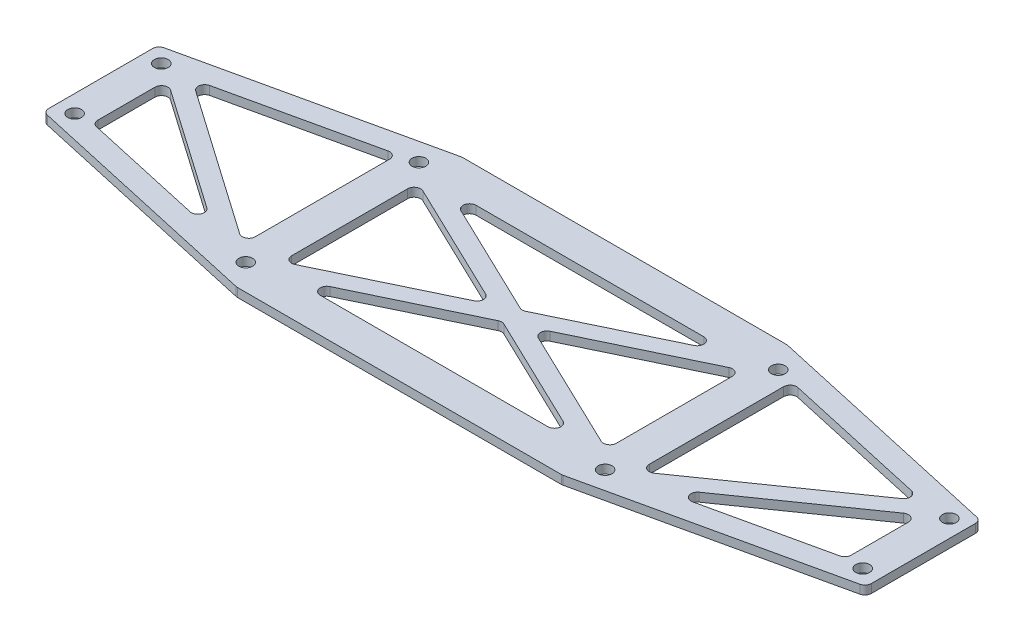
SolidWorks part; units mm, degrees
material "Thornel Mat VMA"
ref_plane "前视基准面" through (0, 0, 0) normal (0, 0, 1) x (1, 0, 0)
ref_plane "上视基准面" through (0, 0, 0) normal (0, 1, 0) x (1, 0, 0)
ref_plane "右视基准面" through (0, 0, 0) normal (1, 0, 0) x (0, 0, -1)
other "Configuration Table"
sketch "草图1" plane through (0, 0, 0) normal (0, 1, 0) x (1, 0, 0)
  line L1 (-95, 26) -> (95, 26)
  line L2 (-95, 26) -> (-95, -26)
  line L3 (-95, -26) -> (95, -26)
  line L4 (95, 26) -> (95, -26)
  line L5 (-95, 26) -> (95, -26) construction
  line L6 (-95, -26) -> (95, 26) construction
  line L7 (-91, 10) -> (91, 10) construction
  line L8 (-91, 10) -> (-91, -10) construction
  line L9 (-91, -10) -> (91, -10) construction
  line L10 (91, 10) -> (91, -10) construction
  line L11 (-91, 10) -> (91, -10) construction
  line L12 (-91, -10) -> (91, 10) construction
  line L13 (-41.5, 20) -> (41.5, 20) construction
  line L14 (-41.5, 20) -> (-41.5, -20) construction
  line L15 (-41.5, -20) -> (41.5, -20) construction
  line L16 (41.5, 20) -> (41.5, -20) construction
  line L17 (-41.5, 20) -> (41.5, -20) construction
  line L18 (-41.5, -20) -> (41.5, 20) construction
  line L19 (-37.5, 18) -> (37.5, 18)
  line L20 (-37.5, 18) -> (-37.5, -18)
  line L21 (-37.5, -18) -> (37.5, -18)
  line L22 (37.5, 18) -> (37.5, -18)
  line L23 (-37.5, 18) -> (37.5, -18) construction
  line L24 (-37.5, -18) -> (37.5, 18) construction
  circle A0 centre (91, -10) radius 1.6
  circle A1 centre (91, 10) radius 1.6
  circle A2 centre (-91, 10) radius 1.6
  circle A3 centre (-91, -10) radius 1.6
  circle A4 centre (41.5, -20) radius 1.6
  circle A5 centre (-41.5, -20) radius 1.6
  circle A6 centre (-41.5, 20) radius 1.6
  circle A7 centre (41.5, 20) radius 1.6
  point P0 (0, 0)
  point P6 (0, 0)
  point P15 (0, 0)
  point P24 (0, 0)
  dimension "D3" = 3.2
  dimension "D1" = 182
  dimension "D2" = 20
  dimension "D4" = 4
  dimension "D5" = 40
  dimension "D6" = 83
  dimension "D7" = 6
  dimension "D8" = 4
  dimension "D9" = 4
extrude "凸台-拉伸1" add sketch "草图1" along normal blind 2
sketch "草图2" plane through (0, 2, 0) normal (0, 1, 0) x (1, 0, 0)
  line L0 (95, 13.2071) -> (37.5601, 26)
  line L1 (95, -26) -> (95, 26) construction
  line L2 (95, 26) -> (-95, 26) construction
  line L3 (37.5601, 26) -> (95, 26)
  line L4 (95, 26) -> (95, 13.2071)
  line L5 (0, 0) -> (0, 43.9826) construction
  line L6 (0, 0) -> (28.9359, 0) construction
  line L7 (37.5601, -26) -> (95, -26)
  line L8 (95, -13.2071) -> (37.5601, -26)
  line L9 (95, -26) -> (95, -13.2071)
  line L10 (-95, -26) -> (-95, -13.2071)
  line L11 (-95, -13.2071) -> (-37.5601, -26)
  line L12 (-37.5601, -26) -> (-95, -26)
  line L13 (-95, 26) -> (-95, 13.2071)
  line L14 (-37.5601, 26) -> (-95, 26)
  line L15 (-95, 13.2071) -> (-37.5601, 26)
  line L16 (45.5, 19.1091) -> (45.5, -19.1091)
  line L17 (45.5, -19.1091) -> (87, -9.8664)
  line L18 (87, -9.8664) -> (87, 9.8664)
  line L19 (87, 9.8664) -> (45.5, 19.1091)
  line L20 (-87, -9.8664) -> (-87, 9.8664)
  line L21 (-45.5, -19.1091) -> (-87, -9.8664)
  line L22 (-45.5, 19.1091) -> (-45.5, -19.1091)
  line L23 (-87, 9.8664) -> (-45.5, 19.1091)
  circle A0 centre (91, 10) radius 1.6 construction
  circle A1 centre (41.5, 20) radius 1.6 construction
  circle A2 centre (91, -10) radius 1.6 construction
  circle A3 centre (41.5, -20) radius 1.6 construction
  point P29 (87, 0)
  dimension "D2" = 5
  dimension "D1" = 4
  dimension "D3" = 4
  dimension "D4" = 5
  dimension "D5" = 4
extrude "切除-拉伸1" cut sketch "草图2" against normal blind 2
sketch "草图3" plane through (0, 2, 0) normal (0, 1, 0) x (1, 0, 0)
  line L0 (-45.5, -19.1091) -> (-87, 9.8664)
  line L1 (37.5, 18) -> (-37.5, -18)
  line L2 (-37.5, 18) -> (37.5, -18)
  line L3 (45.5, -19.1091) -> (87, 9.8664)
extrude "拉伸-薄壁1" add sketch "草图3" against normal blind 2 thin thin type mid plane wall 4
fillet "圆角1" radius 1.5 32 edges at (-95, 1, 13.2071) (-37.5601, 1, 26) (95, 1, 13.2071) (95, 1, -13.2071) (37.5601, 1, -26) (-37.5601, 1, -26) (-95, 1, -13.2071) (37.5601, 1, 26) (-84.3513, 1, -10.4563) (-45.5, 1, -19.1091) (-45.5, 1, 16.6699) (-87, 1, 9.8664) (-87, 1, -7.4271) (-50.63, 1, 17.9666) (32.8782, 1, 18) (-32.8782, 1, 18) (-37.5, 1, -15.7815) (-4.6218, 1, 0) (-37.5, 1, 15.7815) (37.5, 1, 15.7815) (4.6218, 1, 0) (37.5, 1, -15.7815) (0, 1, -2.2185) (-32.8782, 1, -18) (32.8782, 1, -18) (45.5, 1, -19.1091) (84.3513, 1, -10.4563) (45.5, 1, 16.6699) (87, 1, -7.4271) (87, 1, 9.8664) (50.63, 1, 17.9666) (0, 1, 2.2185)
